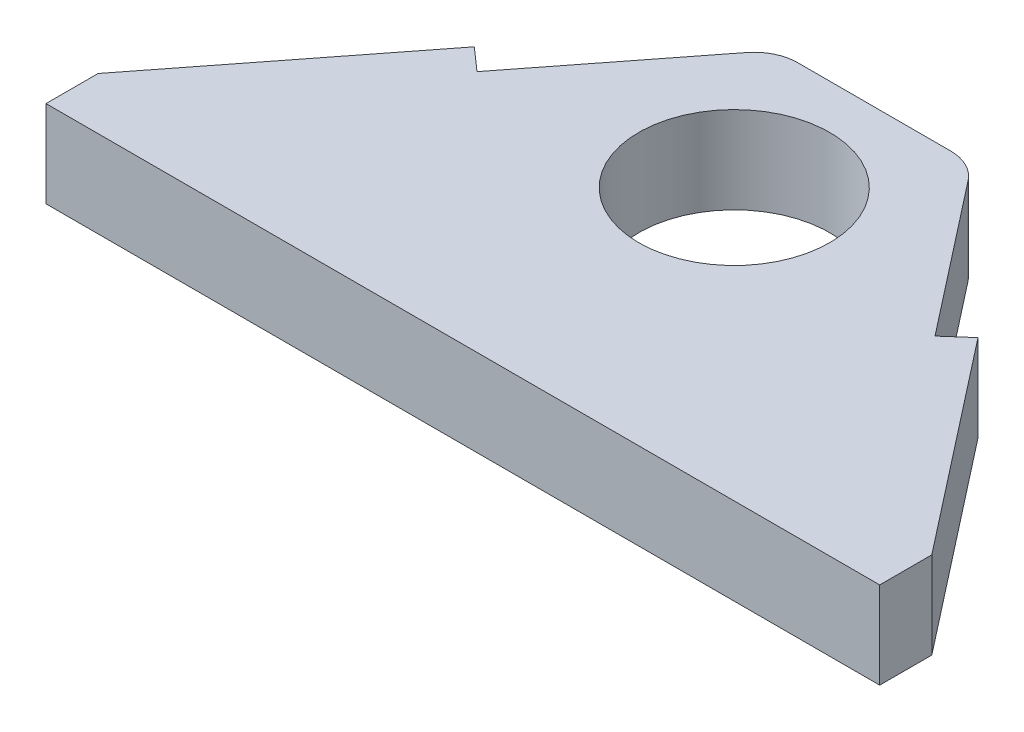
SolidWorks part; units mm, degrees
ref_plane "Front Plane" through (0, 0, 0) normal (0, 0, 1) x (1, 0, 0)
ref_plane "Top Plane" through (0, 0, 0) normal (0, 1, 0) x (1, 0, 0)
ref_plane "Right Plane" through (0, 0, 0) normal (1, 0, 0) x (0, 0, -1)
sketch "Sketch1" plane through (0, 0, 0) normal (0, 1, 0) x (1, 0, 0)
  line L0 (0, -62.5) -> (0, 62.5) construction
  line L1 (-45.2526, 0) -> (45.2526, 0) construction
  line L2 (96, -62.5) -> (-96, -62.5)
  line L3 (-96, -62.5) -> (-96, -50.5)
  line L4 (-96, -50.5) -> (-57.9983, -1.86)
  line L5 (-57.9983, -1.86) -> (-52.7403, -6.5)
  line L6 (-52.7403, -6.5) -> (-32.5826, 19.3007)
  line L9 (-32.5826, 19.3007) -> (-25.4964, 28.3706)
  line L10 (17.6163, 32.214) -> (-17.6163, 32.214)
  line L11 (32.5826, 19.3007) -> (25.4964, 28.3706)
  line L14 (52.7403, -6.5) -> (32.5826, 19.3007)
  line L15 (57.9983, -1.86) -> (52.7403, -6.5)
  line L16 (96, -50.5) -> (57.9983, -1.86)
  line L17 (96, -62.5) -> (96, -50.5)
  circle A0 centre (0, 0) radius 22
  arc A2 (-17.6163, 32.214) -> (-25.4964, 28.3706) centre (-17.6163, 22.214) ccw
  arc A4 (17.6163, 32.214) -> (25.4964, 28.3706) centre (17.6163, 22.214) cw
  point P4 (0, 0)
  point P8 (0, 0)
  point P18 (-22, 31.2019)
  point P19 (22, 31.2019)
  point P22 (0, 0)
  point P26 (0, 32.214)
  point P34 (0, 0)
  point P35 (0, 0)
  dimension "D1" = 44
  dimension "D9" = 10
  dimension "D2" = 96
  dimension "D4" = 38
  dimension "D5" = 7
  dimension "D6" = 12
  dimension "D7" = 56
  dimension "D8" = 60.64
  dimension "D10" = 62.5
  dimension "D11" = 44
  dimension "D12" = 105.4806
  dimension "D13" = 115.9965
extrude "Boss-Extrude1" add sketch "Sketch1" along normal blind 20
